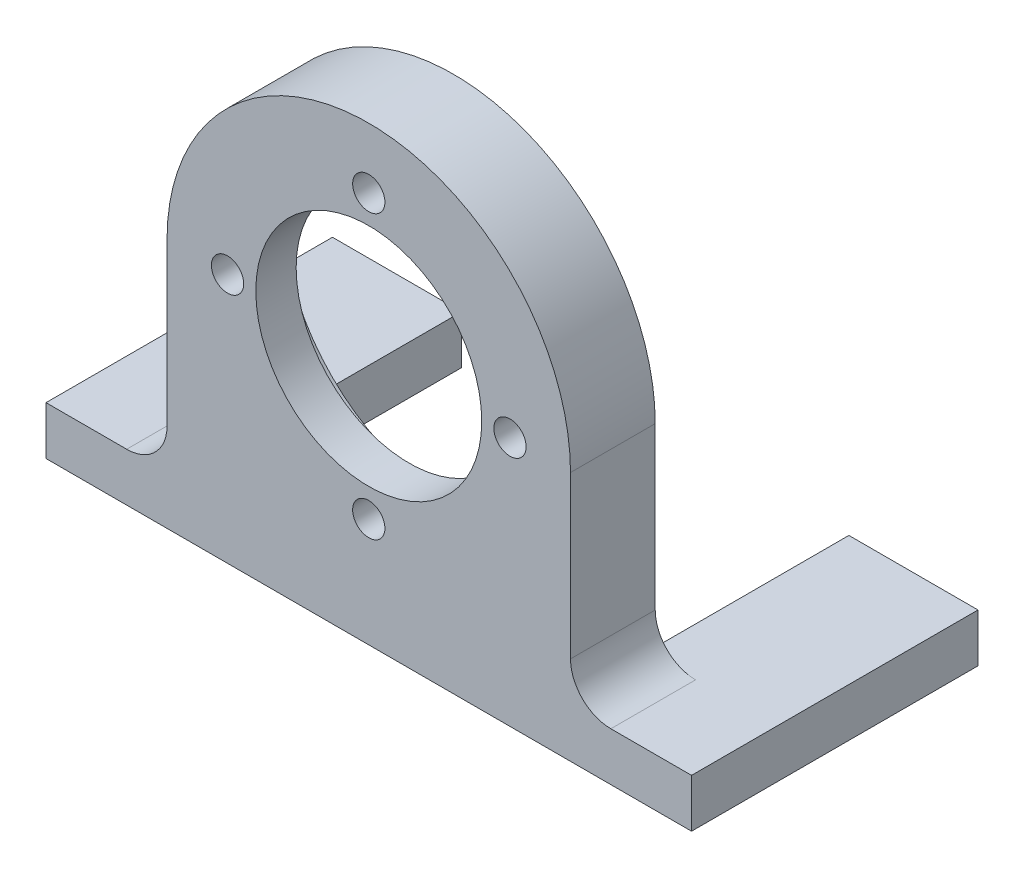
SolidWorks part; units mm, degrees
material "1060 合金"
ref_plane "前视基准面" through (0, 0, 0) normal (0, 0, 1) x (1, 0, 0)
ref_plane "上视基准面" through (0, 0, 0) normal (0, 1, 0) x (1, 0, 0)
ref_plane "右视基准面" through (0, 0, 0) normal (1, 0, 0) x (0, 0, -1)
sketch "草图1" plane through (0, 0, 0) normal (0, 0, 1) x (1, 0, 0)
  line L0 (-25, 0) -> (-25, -25)
  line L5 (25, 0) -> (25, -25)
  line L6 (-25, -25) -> (-40, -25)
  line L7 (-40, -25) -> (-40, -31)
  line L8 (-40, -31) -> (40, -31)
  line L9 (40, -31) -> (40, -25)
  line L10 (40, -25) -> (25, -25)
  arc A0 (25, 0) -> (-25, 0) centre (0, 0) ccw
  dimension "D1" = 50
  dimension "D2" = 15
  dimension "D3" = 15
  dimension "D4" = 25
  dimension "D5" = 25
  dimension "D6" = 6
extrude "凸台-拉伸1" add sketch "草图1" along normal blind 10.5
sketch "草图2" plane through (0, 0, 10.5) normal (0, 0, 1) x (1, 0, 0)
  circle A0 centre (0, 0) radius 14
  dimension "D1" = 28
extrude "切除-拉伸1" cut sketch "草图2" against normal through all
sketch "草图3" plane through (0, 0, 0) normal (0, 0, -1) x (-1, 0, 0)
  circle A0 centre (0, 0) radius 21.25
  dimension "D1" = 42.5
extrude "切除-拉伸2" cut sketch "草图3" against normal blind 5.5
sketch "草图4" plane through (0, 0, 10.5) normal (0, 0, 1) x (1, 0, 0)
  circle A0 centre (0, 17.5) radius 2
  circle A1 centre (17.5, 0) radius 2
  circle A2 centre (0, -17.5) radius 2
  circle A3 centre (-17.5, 0) radius 2
  dimension "D2" = 4
  dimension "D1" = 17.5
  dimension "D3" = 4
extrude "切除-拉伸3" cut sketch "草图4" against normal through all
fillet "圆角1" radius 5 2 edges at (-25, -25, 5.25) (25, -25, 5.25)
sketch "草图5" plane through (0, 0, 0) normal (0, 0, -1) x (-1, 0, 0)
  line L0 (40, -31) -> (-40, -31) construction
  line L1 (40, -25) -> (24, -25)
  line L2 (40, -25) -> (40, -31)
  line L3 (40, -31) -> (24, -31)
  line L4 (24, -25) -> (24, -31)
  line L6 (-40, -25) -> (-24, -25)
  line L7 (-40, -25) -> (-40, -31)
  line L8 (-40, -31) -> (-24, -31)
  line L9 (-24, -25) -> (-24, -31)
  dimension "D1" = 16
  dimension "D2" = 16
extrude "凸台-拉伸2" add sketch "草图5" along normal blind 25
